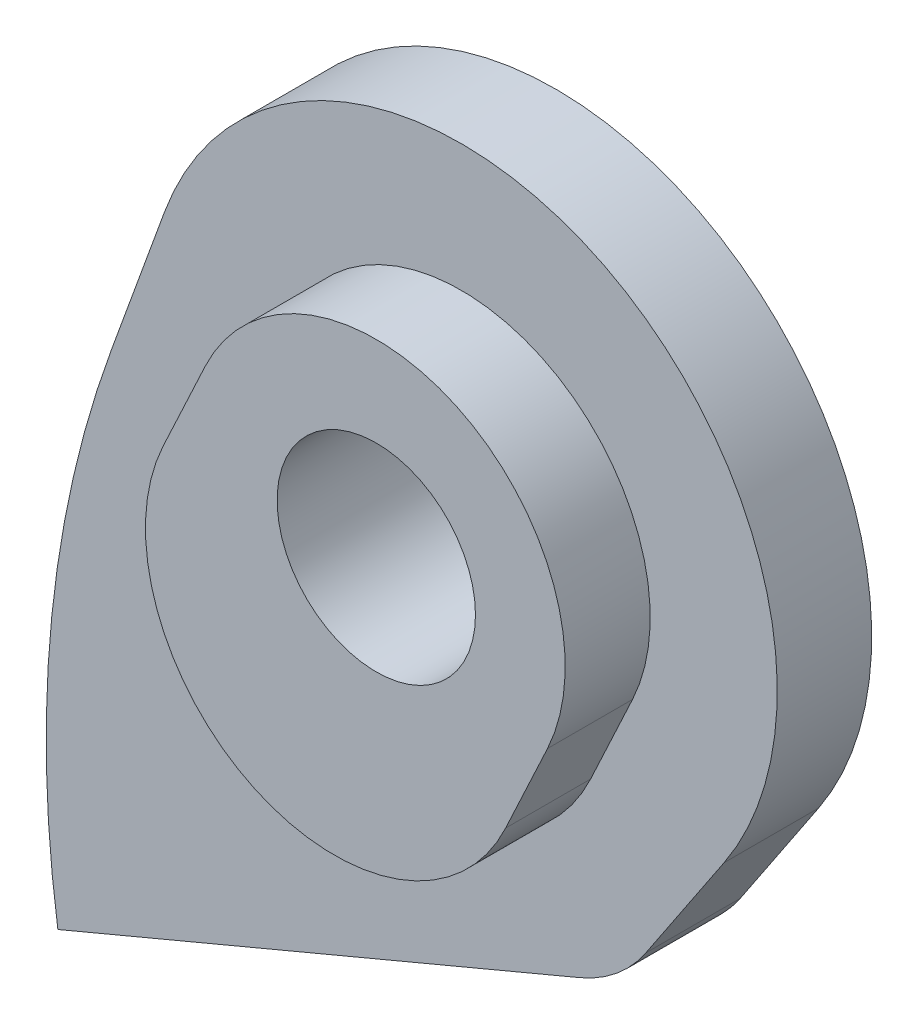
SolidWorks part; units mm, degrees
ref_plane "Front Plane" through (0, 0, 0) normal (0, 0, 1) x (1, 0, 0)
ref_plane "Top Plane" through (0, 0, 0) normal (0, 1, 0) x (1, 0, 0)
ref_plane "Right Plane" through (0, 0, 0) normal (1, 0, 0) x (0, 0, -1)
sketch "Sketch6" plane through (0, 0, 0) normal (0, 0, 1) x (1, 0, 0)
  line L0 (0, 0) -> (40.1809, 0) construction
  line L1 (0, 0) -> (35.507, 92.499) construction
  line L2 (19.3519, 50.4133) -> (0.4719, 63.0164) construction
  line L3 (19.3519, 50.4133) -> (-36.1025, 71.7003) construction
  dimension "D1" = 69
  dimension "D2" = 54
  dimension "D3" = 22.7
  dimension "D4" = 5
sketch "Sketch3" plane through (0, 0, 0) normal (0, 0, 1) x (1, 0, 0)
  line L0 (24.1743, 72.523) -> (120.8717, 72.523) construction
  line L6 (11.8164, 60.2529) -> (11.7284, 60.3116)
  line L7 (7.3748, 53.5992) -> (5.9136, 54.5745)
  line L8 (19.3519, 50.4133) -> (0.4719, 63.0164) construction
  line L9 (-6.1719, 82.4206) -> (-7.2903, 79.3479)
  line L10 (19.3519, 50.4133) -> (13.2479, 41.2693) construction
  line L11 (19.3519, 50.4133) -> (31.6629, 68.8558) construction
  line L12 (4.0204, 73.9337) -> (5.6789, 76.4182)
  line L14 (0.1147, 80.1325) -> (27.1455, 62.0885) construction
  line L15 (0.1147, 80.1325) -> (-7.2903, 79.3479) construction
  line L16 (0.1147, 80.1325) -> (0.1147, 91.1913) construction
  line L17 (0.1147, 80.1325) -> (-6.1719, 82.4206) construction
  arc A0 (13.4996, 47.0498) -> (20.2139, 57.1081) centre (19.3519, 50.4133) ccw
  arc A1 (20.2139, 57.1081) -> (11.8164, 60.2529) centre (22.7223, 76.5904) cw
  arc A2 (13.4996, 47.0498) -> (7.3748, 53.5992) centre (-3.5311, 37.2616) ccw
  arc A3 (11.7284, 60.3116) -> (6.8662, 65.9311) centre (19.4923, 71.9424) cw
  arc A4 (-6.1719, 82.4206) -> (5.6789, 76.4182) centre (0.1147, 80.1325) cw
  arc A5 (6.8662, 65.9311) -> (4.9012, 68.3908) centre (0.6246, 62.9595) ccw
  arc A6 (4.9012, 68.3908) -> (4.0204, 73.9337) centre (7.4585, 71.6386) cw
  arc A7 (5.9136, 54.5745) -> (0.4148, 56.2666) centre (0.3298, 46.2096) ccw
  arc A10 (0.4148, 56.2666) -> (-5.2798, 59.4837) centre (0.4719, 63.0164) cw
  circle A12 centre (19.3519, 50.4133) radius 2.75
  circle A13 centre (0.4719, 63.0164) radius 2.75
  circle A17 centre (0.1147, 80.1325) radius 2.1
  arc A18 (-7.2903, 79.3479) -> (-5.2798, 59.4837) centre (14.2795, 71.4971) ccw
  dimension "D1" = 5.5
  dimension "D2" = 5.5
  dimension "D3" = 4
  dimension "D5" = 4
  dimension "D6" = 4
  dimension "D4" = 4.2
  dimension "D17" = 70
  dimension "D18" = 3.27
  dimension "D14" = 6.69
  dimension "D7" = 3
  dimension "D8" = 4
  dimension "D9" = 3
  dimension "D10" = 4
  dimension "D11" = 19
  dimension "D12" = 19
  dimension "D13" = 22
  dimension "D15" = 32.5
  dimension "D16" = 14
extrude "Boss-Extrude2" add sketch "Sketch3" along normal blind 11
sketch "Sketch13" plane through (0, 0, 0) normal (0, 0, -1) x (-1, 0, 0)
  line L0 (-5.6789, 76.4182) -> (-4.0204, 73.9337)
  line L1 (-2.6258, 72.7829) -> (8.4277, 68.1397)
  line L2 (6.1719, 82.4206) -> (7.2903, 79.3479)
  arc A0 (-5.6789, 76.4182) -> (6.1719, 82.4206) centre (-0.1147, 80.1325) cw
  arc A1 (6.1719, 82.4206) -> (-5.6789, 76.4182) centre (-0.1147, 80.1325) ccw construction
  arc A2 (-4.0204, 73.9337) -> (-2.6258, 72.7829) centre (-1.4106, 75.6758) ccw
  arc A3 (5.2798, 59.4837) -> (7.2903, 79.3479) centre (-14.2795, 71.4971) ccw construction
  arc A4 (8.4277, 68.1397) -> (7.2903, 79.3479) centre (-14.2795, 71.4971) ccw
extrude "Boss-Extrude4" add sketch "Sketch13" along normal blind 2
sketch "Sketch12" plane through (0, 0, -2) normal (0, 0, -1) x (-1, 0, 0)
  line L0 (8.0136, 76.9658) -> (4.9242, 69.6114)
  line L4 (4.9242, 69.6114) -> (8.4277, 68.1397)
  line L5 (-2.6258, 72.7829) -> (8.4277, 68.1397) construction
  line L8 (-2.6258, 72.7829) -> (8.4277, 68.1397) construction
  arc A0 (8.0136, 76.9658) -> (8.4277, 68.1397) centre (-14.2795, 71.4971) cw
  arc A1 (5.2798, 59.4837) -> (8.4277, 68.1397) centre (-14.2795, 71.4971) ccw construction
  dimension "D1" = 3.8
  dimension "D2" = 90
extrude "Boss-Extrude3" add sketch "Sketch12" along normal blind 3
sketch "Sketch14" plane through (0, 0, 0) normal (0, 1, 0) x (1, 0, 0)
  line L0 (19.3519, 0) -> (-36.1025, 0) construction
  line L1 (-15.2308, 0) -> (32.0549, 0)
  line L2 (-15.2308, 0) -> (-15.2308, -12.5955)
  line L3 (-15.2308, -12.5955) -> (32.0549, -12.5955)
  line L4 (32.0549, 0) -> (32.0549, -12.5955)
extrude "Cut-Extrude1" cut sketch "Sketch14" along normal through all
sketch "Sketch16" plane through (0, 0, 0) normal (0, 0, 1) x (1, 0, 0)
  line L0 (0.1147, 80.1325) -> (-0.7728, 78.2293) construction
  line L1 (3.7399, 78.4421) -> (2.8524, 76.5388)
  line L2 (-3.5105, 81.823) -> (-4.398, 79.9198)
  line L3 (0.1147, 80.1325) -> (0.1147, 75.6752) construction
  arc A0 (3.7399, 78.4421) -> (-3.5105, 81.823) centre (0.1147, 80.1325) ccw
  arc A1 (-4.398, 79.9198) -> (2.8524, 76.5388) centre (-0.7728, 78.2293) ccw
  point P3 (-0.3291, 79.1809)
  dimension "D1" = 4
  dimension "D2" = 25
  dimension "D3" = 2.1
extrude "Boss-Extrude5" add sketch "Sketch16" along normal blind 1.8
sketch "Sketch15" plane through (0, 0, 1.8) normal (0, 0, 1) x (1, 0, 0)
  circle A0 centre (0.1147, 80.1325) radius 2.1
  dimension "D1" = 4.2
extrude "Cut-Extrude2" cut sketch "Sketch15" against normal through all
